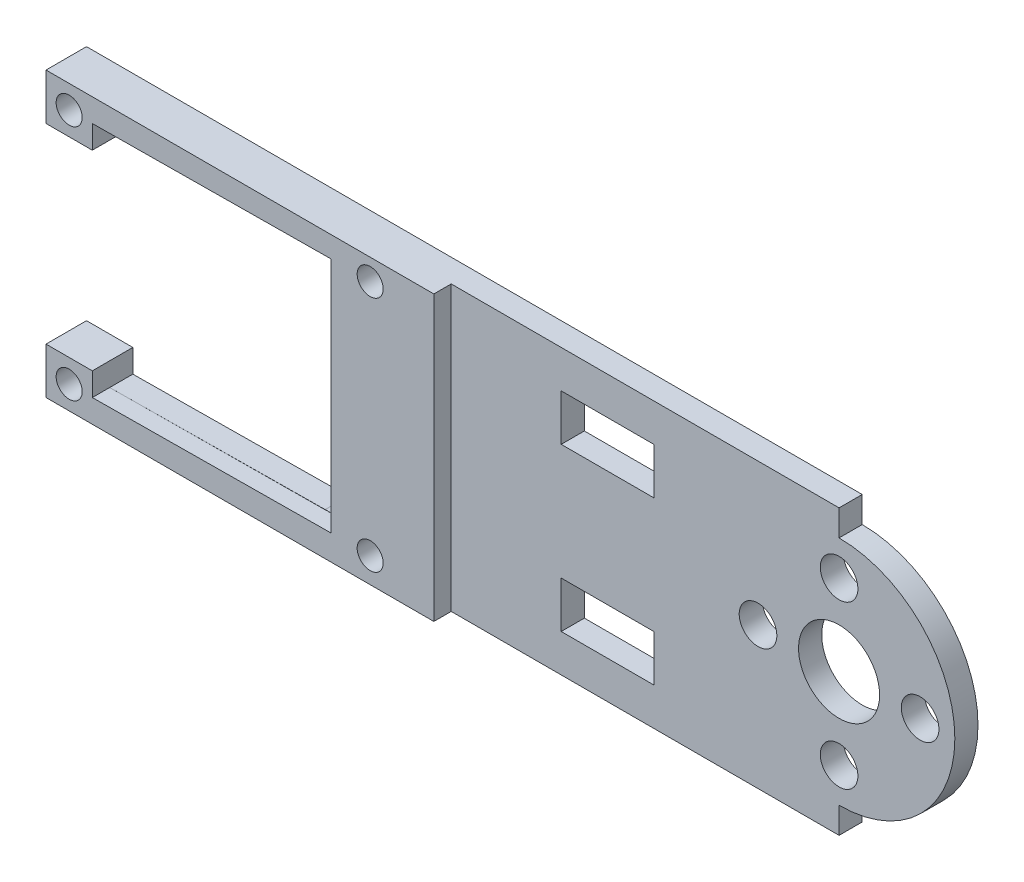
SolidWorks part; units mm, degrees
ref_plane "Front Plane" through (0, 0, 0) normal (0, 0, 1) x (1, 0, 0)
ref_plane "Top Plane" through (0, 0, 0) normal (0, 1, 0) x (1, 0, 0)
ref_plane "Right Plane" through (0, 0, 0) normal (1, 0, 0) x (0, 0, -1)
sketch "Sketch1" plane through (0, 0, 0) normal (0, 0, 1) x (1, 0, 0)
  line L6 (-29, -8.25) -> (-29, -12.25)
  line L12 (-29, 12.25) -> (38, 12.25)
  line L13 (38, 12.25) -> (38, 10)
  line L14 (38, -12.25) -> (-29, -12.25)
  line L16 (38, -10) -> (38, -12.25)
  line L17 (14, 9) -> (22, 9)
  line L18 (14, 9) -> (14, 5)
  line L19 (14, 5) -> (22, 5)
  line L20 (22, 9) -> (22, 5)
  line L21 (14, 9) -> (22, 5) construction
  line L22 (14, 5) -> (22, 9) construction
  line L23 (14, -5) -> (22, -5)
  line L24 (14, -5) -> (14, -9)
  line L25 (14, -9) -> (22, -9)
  line L26 (22, -5) -> (22, -9)
  line L27 (14, -5) -> (22, -9) construction
  line L28 (14, -9) -> (22, -5) construction
  line L44 (-29, 12.25) -> (-29, 8.25)
  line L45 (-29, 8.25) -> (-25, 8.25)
  line L46 (-25, 8.25) -> (-25, 10.25)
  line L51 (-25, -8.25) -> (-25, -10.25)
  line L53 (-25, 10.25) -> (-6.3849, 10.4292)
  line L54 (-6.3849, -10.0708) -> (-25, -10.25)
  line L55 (-29, -8.25) -> (-25, -8.25)
  line L56 (-6.3849, 10.4292) -> (-4.3835, 10.4292)
  line L57 (-4.3835, 10.4292) -> (-4.3835, -10.0708)
  line L58 (-4.3835, -10.0708) -> (-6.3849, -10.0708)
  arc A2 (38, -10) -> (38, 10) centre (38, 0) ccw
  circle A3 centre (38, 7) radius 1.625
  circle A4 centre (45, 0) radius 1.625
  circle A5 centre (38, -7) radius 1.625
  circle A6 centre (31, 0) radius 1.625
  circle A7 centre (38, 0) radius 3.5
  circle A10 centre (-27, 10.25) radius 1.125
  circle A11 centre (-27, -10.25) radius 1.125
  circle A12 centre (-1, 10.4292) radius 1.125
  circle A13 centre (-1, -10.0708) radius 1.125
  point P4 (0, 0)
  point P22 (18, 7)
  point P35 (18, -7)
  dimension "D4" = 2.25
  dimension "D11" = 20
  dimension "D12" = 3.25
  dimension "D15" = 7
  dimension "D30" = 2.25
  dimension "D31" = 4
  dimension "D6" = 2.25
  dimension "D7" = 2.25
  dimension "D8" = 2.25
  dimension "D17" = 1
  dimension "D5" = 2.25
  dimension "D9" = 2
  dimension "D10" = 4
  dimension "D13" = 7
  dimension "D16" = 2
  dimension "D18" = 2.0014
  dimension "D19" = 20
  dimension "D20" = 4
  dimension "D21" = 4
  dimension "D22" = 8
  dimension "D23" = 8
  dimension "D24" = 38
  dimension "D25" = 20.5
  dimension "D26" = 2
  dimension "D27" = 2
  dimension "D28" = 4
  dimension "D29" = 4
  dimension "D32" = 12.25
  dimension "D33" = 20.5
  dimension "D34" = 67
  dimension "D14" = 4
extrude "Boss-Extrude1" add sketch "Sketch1" along normal blind 2
sketch "Sketch8" plane through (0, 0, 2) normal (0, 0, 1) x (1, 0, 0)
  line L0 (-29, 12.25) -> (4.5, 12.25)
  line L1 (-29, 12.25) -> (38, 12.25) construction
  line L2 (4.5, 12.25) -> (4.5, -12.25)
  line L3 (38, -12.25) -> (-29, -12.25) construction
  line L4 (4.5, -12.25) -> (-29, -12.25)
  line L5 (-29, -12.25) -> (-29, -8.25)
  line L6 (-29, -8.25) -> (-25, -8.25)
  line L7 (-25, -8.25) -> (-25, -10.25)
  line L8 (-25, -10.25) -> (-4.3835, -10.0708)
  line L9 (-4.3835, -10.0708) -> (-4.3835, 10.4292)
  line L10 (-4.3835, 10.4292) -> (-25, 10.25)
  line L11 (-25, 10.25) -> (-25, 8.25)
  line L12 (-25, 8.25) -> (-29, 8.25)
  line L13 (-29, 8.25) -> (-29, 12.25)
  circle A0 centre (-27, 10.25) radius 1.125
  circle A1 centre (-27, -10.25) radius 1.125
  circle A2 centre (-1, 10.4292) radius 1.125
  circle A3 centre (-1, -10.0708) radius 1.125
extrude "Boss-Extrude4" add sketch "Sketch8" along normal blind 1.5
